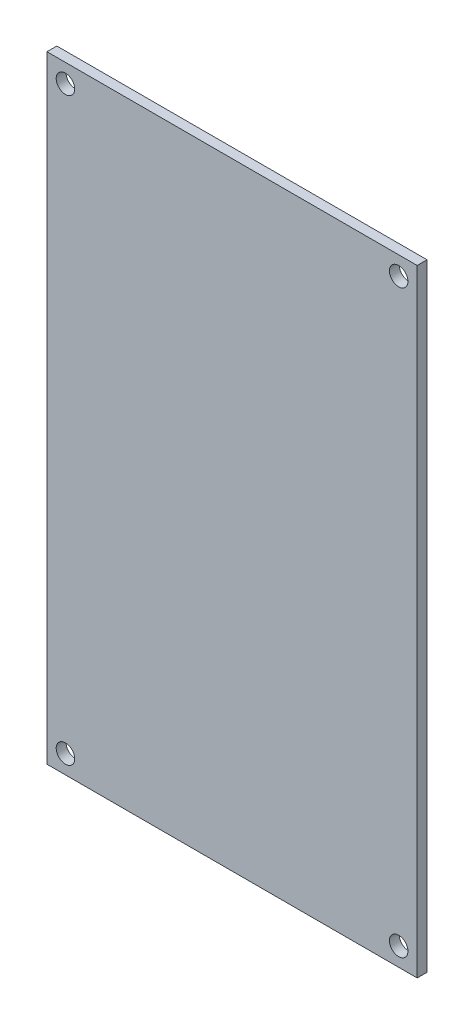
SolidWorks part; units mm, degrees
ref_plane "前视基准面" through (0, 0, 0) normal (0, 0, 1) x (1, 0, 0)
ref_plane "上视基准面" through (0, 0, 0) normal (0, 1, 0) x (1, 0, 0)
ref_plane "右视基准面" through (0, 0, 0) normal (1, 0, 0) x (0, 0, -1)
sketch "草图1" plane through (0, 0, 0) normal (0, 0, 1) x (1, 0, 0)
  line L1 (0, 0) -> (60, 0)
  line L2 (0, 0) -> (0, 100)
  line L3 (0, 100) -> (60, 100)
  line L4 (60, 0) -> (60, 100)
  circle A0 centre (3, 3) radius 1.5
  circle A1 centre (57, 3) radius 1.5
  circle A2 centre (57, 97) radius 1.5
  circle A3 centre (3, 97) radius 1.5
  dimension "D3" = 3
  dimension "D6" = 3
  dimension "D9" = 3
  dimension "D14" = 3
  dimension "D1" = 60
  dimension "D2" = 100
  dimension "D4" = 3
  dimension "D5" = 3
  dimension "D7" = 3
  dimension "D8" = 3
  dimension "D10" = 3
  dimension "D11" = 3
  dimension "D12" = 3
  dimension "D13" = 3
extrude "凸台-拉伸1" add sketch "草图1" along normal blind 1.6
